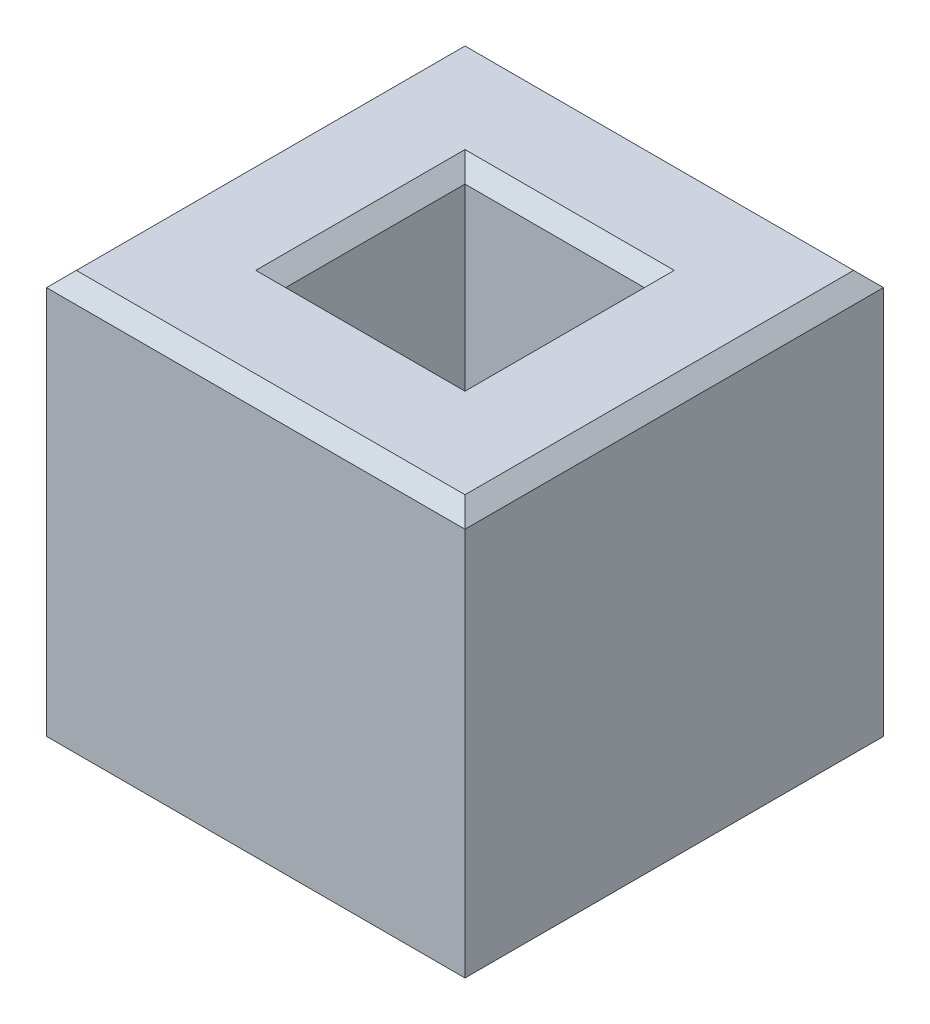
SolidWorks part; units mm, degrees
ref_plane "Front Plane" through (0, 0, 0) normal (0, 0, 1) x (1, 0, 0)
ref_plane "Top Plane" through (0, 0, 0) normal (0, 1, 0) x (1, 0, 0)
ref_plane "Right Plane" through (0, 0, 0) normal (1, 0, 0) x (0, 0, -1)
sketch "Sketch2" plane through (0, 0, 0) normal (0, 1, 0) x (1, 0, 0)
  line L1 (-88.9, -88.9) -> (88.9, -88.9)
  line L2 (-88.9, -88.9) -> (-88.9, 88.9)
  line L3 (-88.9, 88.9) -> (88.9, 88.9)
  line L4 (88.9, -88.9) -> (88.9, 88.9)
  line L5 (-88.9, -88.9) -> (88.9, 88.9) construction
  line L6 (-88.9, 88.9) -> (88.9, -88.9) construction
  point P0 (0, 0)
  dimension "D1" = 177.8
extrude "Boss-Extrude1" add sketch "Sketch2" along normal blind 177.8
sketch "Sketch3" plane through (0, 177.8, 0) normal (0, 1, 0) x (1, 0, 0)
  line L1 (-38.1, -38.1) -> (38.1, -38.1)
  line L2 (-38.1, -38.1) -> (-38.1, 38.1)
  line L3 (-38.1, 38.1) -> (38.1, 38.1)
  line L4 (38.1, -38.1) -> (38.1, 38.1)
  line L5 (-38.1, -38.1) -> (38.1, 38.1) construction
  line L6 (-38.1, 38.1) -> (38.1, -38.1) construction
  point P0 (0, 0)
  dimension "D1" = 76.2
extrude "Cut-Extrude1" cut sketch "Sketch3" against normal through all and the other way through all
chamfer "Chamfer1" distance 6.35 angle 45 16 edges at (0, 177.8, 88.9) (-88.9, 177.8, 0) (0, 177.8, -88.9) (88.9, 177.8, 0) (-38.1, 177.8, 0) (0, 177.8, 38.1) (38.1, 177.8, 0) (0, 177.8, -38.1) (0, 0, -88.9) (-88.9, 0, 0) (0, 0, 88.9) (88.9, 0, 0) (0, 0, 38.1) (-38.1, 0, 0) (0, 0, -38.1) (38.1, 0, 0)
